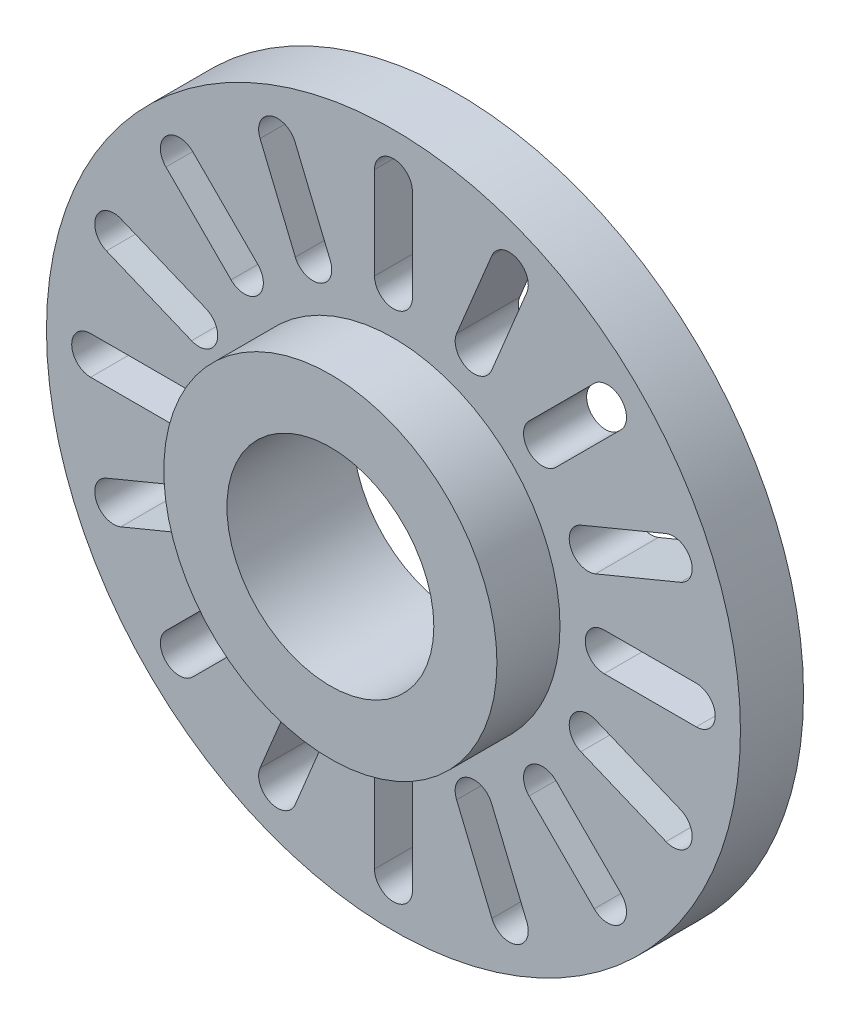
SolidWorks part; units mm, degrees
ref_plane "Front Plane" through (0, 0, 0) normal (0, 0, 1) x (1, 0, 0)
ref_plane "Top Plane" through (0, 0, 0) normal (0, 1, 0) x (1, 0, 0)
ref_plane "Right Plane" through (0, 0, 0) normal (1, 0, 0) x (0, 0, -1)
sketch "Sketch1" plane through (0, 0, 0) normal (0, 0, 1) x (1, 0, 0)
  circle A0 centre (0, 0) radius 4.1
  circle A1 centre (0, 0) radius 13.75
  dimension "D1" = 27.5
  dimension "D2" = 8.2
extrude "Boss-Extrude1" add sketch "Sketch1" along normal blind 2.5
sketch "Sketch2" plane through (0, 0, 2.5) normal (0, 0, 1) x (1, 0, 0)
  circle A0 centre (0, 0) radius 4.1
  circle A1 centre (0, 0) radius 6.6
  circle A2 centre (0, 0) radius 4.1 construction
  dimension "D1" = 2.5
extrude "Boss-Extrude2" add sketch "Sketch2" along normal blind 2.5
sketch "Sketch3" plane through (0, 0, 2.5) normal (0, 0, 1) x (1, 0, 0)
  line L0 (0, 0) -> (0, 4.1) construction
  line L1 (-0.75, 12) -> (-0.75, 8.35)
  line L2 (0.75, 12) -> (0.75, 8.35)
  line L3 (0, 7.6) -> (0, 9.1) construction
  line L4 (0, 9.1) -> (0, 11.25) construction
  line L5 (0, 11.25) -> (0, 12.75) construction
  line L6 (0, 12.75) -> (0, 13.75) construction
  line L7 (0, 4.1) -> (0, 6.6) construction
  line L8 (0, 6.6) -> (0, 7.6) construction
  line L9 (3.8993, 11.3736) -> (2.5025, 8.0014)
  line L10 (5.2851, 10.7995) -> (3.8883, 7.4274)
  line L11 (7.955, 9.0156) -> (5.374, 6.4347)
  line L12 (9.0156, 7.955) -> (6.4347, 5.374)
  line L13 (10.7995, 5.2851) -> (7.4274, 3.8883)
  line L14 (11.3736, 3.8993) -> (8.0014, 2.5025)
  line L15 (12, 0.75) -> (8.35, 0.75)
  line L16 (12, -0.75) -> (8.35, -0.75)
  line L17 (11.3736, -3.8993) -> (8.0014, -2.5025)
  line L18 (10.7995, -5.2851) -> (7.4274, -3.8883)
  line L19 (9.0156, -7.955) -> (6.4347, -5.374)
  line L20 (7.955, -9.0156) -> (5.374, -6.4347)
  line L21 (5.2851, -10.7995) -> (3.8883, -7.4274)
  line L22 (3.8993, -11.3736) -> (2.5025, -8.0014)
  line L23 (0.75, -12) -> (0.75, -8.35)
  line L24 (-0.75, -12) -> (-0.75, -8.35)
  line L25 (-3.8993, -11.3736) -> (-2.5025, -8.0014)
  line L26 (-5.2851, -10.7995) -> (-3.8883, -7.4274)
  line L27 (-7.955, -9.0156) -> (-5.374, -6.4347)
  line L28 (-9.0156, -7.955) -> (-6.4347, -5.374)
  line L29 (-10.7995, -5.2851) -> (-7.4274, -3.8883)
  line L30 (-11.3736, -3.8993) -> (-8.0014, -2.5025)
  line L31 (-12, -0.75) -> (-8.35, -0.75)
  line L32 (-12, 0.75) -> (-8.35, 0.75)
  line L33 (-11.3736, 3.8993) -> (-8.0014, 2.5025)
  line L34 (-10.7995, 5.2851) -> (-7.4274, 3.8883)
  line L35 (-9.0156, 7.955) -> (-6.4347, 5.374)
  line L36 (-7.955, 9.0156) -> (-5.374, 6.4347)
  line L37 (-5.2851, 10.7995) -> (-3.8883, 7.4274)
  line L38 (-3.8993, 11.3736) -> (-2.5025, 8.0014)
  circle A1 centre (0, 12) radius 0.75
  circle A2 centre (0, 8.35) radius 0.75
  circle A3 centre (0, 0) radius 13.75 construction
  circle A4 centre (0, 0) radius 4.1 construction
  circle A5 centre (0, 0) radius 6.6 construction
  circle A6 centre (4.5922, 11.0866) radius 0.75
  circle A7 centre (3.1954, 7.7144) radius 0.75
  circle A8 centre (8.4853, 8.4853) radius 0.75
  circle A9 centre (5.9043, 5.9043) radius 0.75
  circle A10 centre (11.0866, 4.5922) radius 0.75
  circle A11 centre (7.7144, 3.1954) radius 0.75
  circle A12 centre (12, 0) radius 0.75
  circle A13 centre (8.35, 0) radius 0.75
  circle A14 centre (11.0866, -4.5922) radius 0.75
  circle A15 centre (7.7144, -3.1954) radius 0.75
  circle A16 centre (8.4853, -8.4853) radius 0.75
  circle A17 centre (5.9043, -5.9043) radius 0.75
  circle A18 centre (4.5922, -11.0866) radius 0.75
  circle A19 centre (3.1954, -7.7144) radius 0.75
  circle A20 centre (0, -12) radius 0.75
  circle A21 centre (0, -8.35) radius 0.75
  circle A22 centre (-4.5922, -11.0866) radius 0.75
  circle A23 centre (-3.1954, -7.7144) radius 0.75
  circle A24 centre (-8.4853, -8.4853) radius 0.75
  circle A25 centre (-5.9043, -5.9043) radius 0.75
  circle A26 centre (-11.0866, -4.5922) radius 0.75
  circle A27 centre (-7.7144, -3.1954) radius 0.75
  circle A28 centre (-12, 0) radius 0.75
  circle A29 centre (-8.35, 0) radius 0.75
  circle A30 centre (-11.0866, 4.5922) radius 0.75
  circle A31 centre (-7.7144, 3.1954) radius 0.75
  circle A32 centre (-8.4853, 8.4853) radius 0.75
  circle A33 centre (-5.9043, 5.9043) radius 0.75
  circle A34 centre (-4.5922, 11.0866) radius 0.75
  circle A35 centre (-3.1954, 7.7144) radius 0.75
  point P24 (0, 0)
  point P29 (0, 0)
  point P151 (0, 0)
  dimension "D1" = 1.5
  dimension "D2" = 1
  dimension "D3" = 16
extrude "Cut-Extrude1" cut sketch "Sketch3" against normal through all and the other way through all contours A2 L2 A1 L1 | A7 L10 A6 L9 | A9 L12 A8 L11 | A11 L14 A10 L13 | A13 L16 A12 L15 | A15 L18 A14 L17 | A17 L20 A16 L19 | A19 L22 A18 L21 | A21 L24 A20 L23 | A23 L26 A22 L25 | A25 L28 A24 L27 | A27 L30 A26 L29 | A29 L32 A28 L31 | A31 L34 A30 L33 | A33 L36 A32 L35 | A35 L38 A34 L37 | A1 | A6 | A8 | A10 | A11 | A9 | A7 | A2 | A34 | A32 | A30 | A31 | A33 | A35 | A28 | A26 | A24 | A22 | A29 | A27 | A25 | A23 | A19 | A17 | A15 | A13 | A12 | A14 | A16 | A18 | A20 | A21
